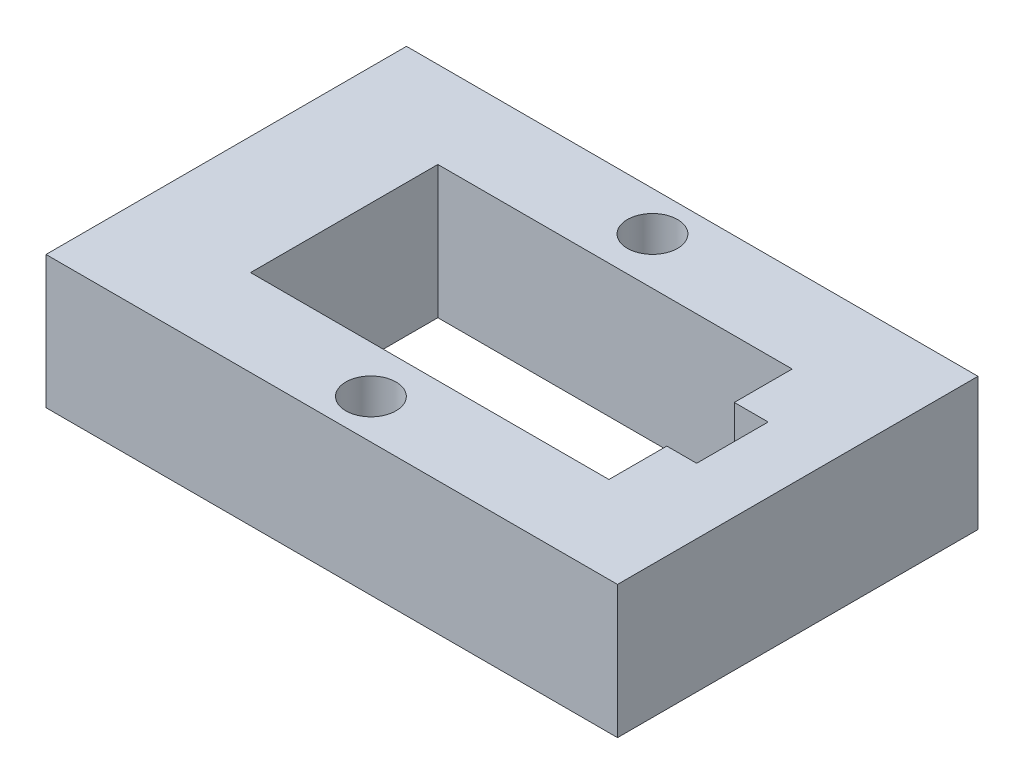
SolidWorks part; units mm, degrees
ref_plane "Front Plane" through (0, 0, 0) normal (0, 0, 1) x (1, 0, 0)
ref_plane "Top Plane" through (0, 0, 0) normal (0, 1, 0) x (1, 0, 0)
ref_plane "Right Plane" through (0, 0, 0) normal (1, 0, 0) x (0, 0, -1)
sketch "Sketch2" plane through (0, 0, 0) normal (0, 1, 0) x (1, 0, 0)
  line L0 (-12.629, 7.7591) -> (11.3956, 7.7591)
  line L1 (-20.629, 13.6321) -> (18.1229, 13.6321)
  line L2 (-20.629, 13.6321) -> (-20.629, -10.8109)
  line L3 (-20.629, -10.8109) -> (18.1229, -10.8109)
  line L4 (18.1229, 13.6321) -> (18.1229, -10.8109)
  line L5 (11.3956, 7.7591) -> (11.3956, 3.8339)
  line L6 (11.3956, 3.8339) -> (13.6929, 3.8339)
  line L7 (13.6929, 3.8339) -> (13.6929, -1.0158)
  line L8 (13.6929, -1.0158) -> (11.671, -1.0158)
  line L9 (11.671, -1.0158) -> (11.671, -4.9409)
  line L10 (11.671, -4.9409) -> (-12.629, -4.9409)
  line L11 (-12.629, -4.9409) -> (-12.629, 7.7591)
  circle A0 centre (-1.2727, 10.9544) radius 1.7
  circle A1 centre (-1.2771, -8.1309) radius 1.7
  dimension "D8" = 3.4
  dimension "D13" = 19.3956
  dimension "D14" = 19.4
  dimension "D2" = 5.87
  dimension "D3" = 12.7
  dimension "D4" = 24.3
  dimension "D5" = 2.0219
  dimension "D6" = 4.8498
  dimension "D7" = 2.6777
  dimension "D9" = 5.873
  dimension "D10" = 2.68
  dimension "D11" = 8
  dimension "D12" = 4.43
extrude "Boss-Extrude1" add sketch "Sketch2" along normal mid plane 9
